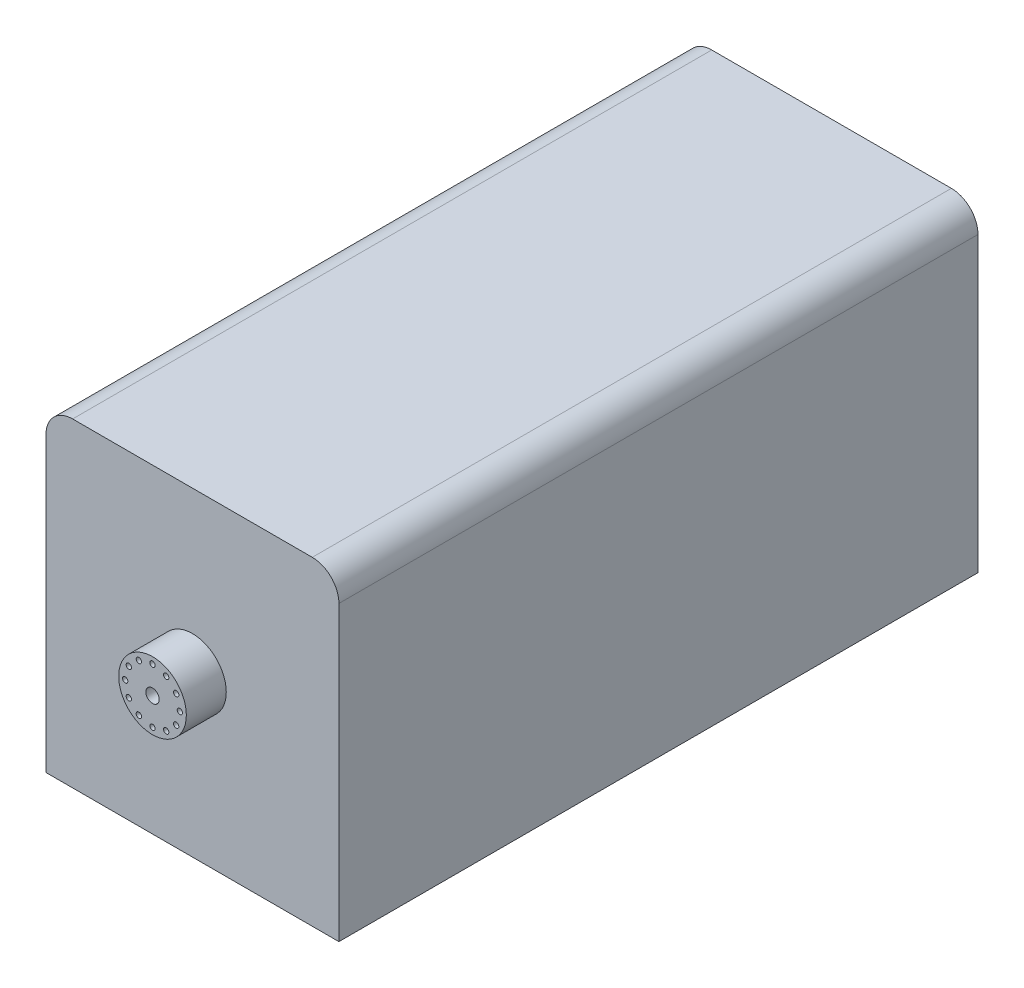
SolidWorks part; units mm, degrees
ref_plane "Front Plane" through (0, 0, 0) normal (0, 0, 1) x (1, 0, 0)
ref_plane "Top Plane" through (0, 0, 0) normal (0, 1, 0) x (1, 0, 0)
ref_plane "Right Plane" through (0, 0, 0) normal (1, 0, 0) x (0, 0, -1)
sketch "Sketch1" plane through (0, 0, 0) normal (0, 0, 1) x (1, 0, 0)
  line L1 (55, 60) -> (-55, 60)
  line L2 (55, 60) -> (55, -60)
  line L3 (55, -60) -> (-55, -60)
  line L4 (-55, 60) -> (-55, -60)
  line L5 (55, 60) -> (-55, -60) construction
  line L6 (55, -60) -> (-55, 60) construction
  point P0 (0, 0)
  dimension "D1" = 110
  dimension "D2" = 120
extrude "Boss-Extrude1" add sketch "Sketch1" along normal blind 240
fillet "Fillet1" radius 10 2 edges at (-55, 60, 120) (55, 60, 120)
sketch "Sketch2" plane through (0, -60, 0) normal (0, -1, 0) x (1, 0, 0)
  circle A0 centre (-37.0591, 221.5691) radius 7.5
  circle A1 centre (32.9409, 221.5691) radius 7.5
  circle A2 centre (32.9409, 21.5691) radius 7.5
  circle A3 centre (-37.0591, 21.5691) radius 7.5
  dimension "D1" = 15
  dimension "D2" = 200
  dimension "D3" = 70
extrude "Boss-Extrude2" add sketch "Sketch2" along normal blind 10
sketch "Sketch3" plane through (0, 0, 240) normal (0, 0, 1) x (1, 0, 0)
  circle A0 centre (0, 0) radius 12.7
  circle A1 centre (0, 0) radius 2.5167
  circle A3 centre (-10.265, 0) radius 1
  circle A4 centre (-8.8898, 5.1325) radius 1
  circle A5 centre (-5.1325, 8.8898) radius 1
  circle A6 centre (0, 10.265) radius 1
  circle A7 centre (5.1325, 8.8898) radius 1
  circle A8 centre (8.8898, 5.1325) radius 1
  circle A9 centre (10.265, 0) radius 1
  circle A10 centre (8.8898, -5.1325) radius 1
  circle A11 centre (5.1325, -8.8898) radius 1
  circle A12 centre (0, -10.265) radius 1
  circle A13 centre (-5.1325, -8.8898) radius 1
  circle A14 centre (-8.8898, -5.1325) radius 1
  point P31 (0, 0)
  dimension "D1" = 25.4
  dimension "D2" = 2
  dimension "D3" = 12
extrude "Boss-Extrude3" add sketch "Sketch3" along normal blind 15
